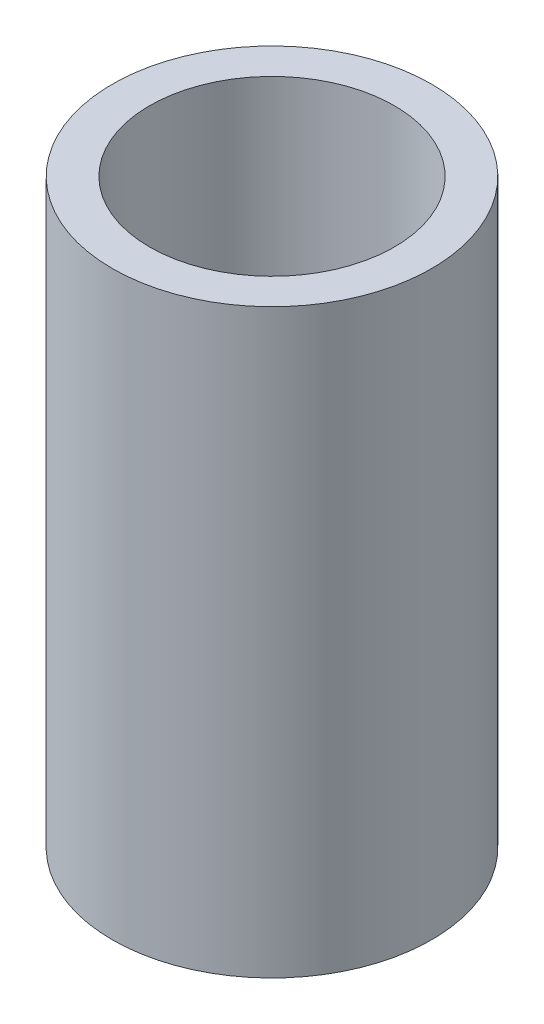
SolidWorks part; units mm, degrees
ref_plane "Front Plane" through (0, 0, 0) normal (0, 0, 1) x (1, 0, 0)
ref_plane "Top Plane" through (0, 0, 0) normal (0, 1, 0) x (1, 0, 0)
ref_plane "Right Plane" through (0, 0, 0) normal (1, 0, 0) x (0, 0, -1)
sketch "Sketch1" plane through (0, 0, 0) normal (0, 1, 0) x (1, 0, 0)
  circle A0 centre (0, 0) radius 2.3
  circle A1 centre (0, 0) radius 3
  dimension "2.3mm*2" = 4.6
  dimension "D2" = 6
extrude "Boss-Extrude1" add sketch "Sketch1" along normal blind 10.922
